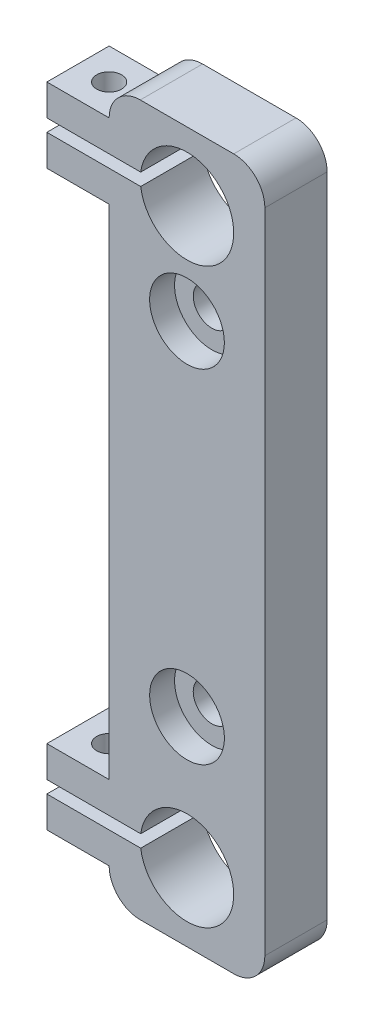
SolidWorks part; units mm, degrees
material "1.0035 (S185)"
ref_plane "前视基准面" through (0, 0, 0) normal (0, 0, 1) x (1, 0, 0)
ref_plane "上视基准面" through (0, 0, 0) normal (0, 1, 0) x (1, 0, 0)
ref_plane "右视基准面" through (0, 0, 0) normal (1, 0, 0) x (0, 0, -1)
sketch "草图1" plane through (0, 0, 0) normal (0, 0, 1) x (1, 0, 0)
  line L1 (-7.5, -57) -> (7.5, -57)
  line L2 (-12.5, -52) -> (-12.5, 52)
  line L3 (-7.5, 57) -> (7.5, 57)
  line L4 (12.5, -52) -> (12.5, 52)
  line L5 (-12.5, -57) -> (12.5, 57) construction
  line L6 (-12.5, 57) -> (12.5, -57) construction
  arc A0 (-7.5, -57) -> (-12.5, -52) centre (-7.5, -52) cw
  arc A1 (7.5, -57) -> (12.5, -52) centre (7.5, -52) ccw
  arc A2 (7.5, 57) -> (12.5, 52) centre (7.5, 52) cw
  arc A3 (-12.5, 52) -> (-7.5, 57) centre (-7.5, 52) cw
  point P0 (0, 0)
  dimension "D3" = 5
  dimension "D1" = 25
  dimension "D2" = 114
extrude "凸台-拉伸1" add sketch "草图1" along normal blind 10
sketch "草图2" plane through (0, 0, 10) normal (0, 0, 1) x (1, 0, 0)
  line L1 (-12.5, 0) -> (12.5, 0) construction
  line L2 (-12.5, 52) -> (-12.5, -52) construction
  line L3 (12.5, -52) -> (12.5, 52) construction
  circle A0 centre (0, 46) radius 7.5
  circle A1 centre (0, -46) radius 7.5
  dimension "D1" = 15
  dimension "D2" = 92
sketch "草图4" plane through (0, 0, 10) normal (0, 0, 1) x (1, 0, 0)
  line L0 (12.5, 0) -> (-12.5, 0) construction
  line L1 (12.5, -52) -> (12.5, 52) construction
  line L2 (-12.5, 52) -> (-12.5, -52) construction
  line L3 (-7.5, -57) -> (7.5, -57) construction
  circle A0 centre (0, 30) radius 3
  circle A4 centre (0, -25) radius 3
  dimension "D1" = 6
  dimension "D2" = 30
  dimension "D3" = 32
extrude "切除-拉伸1" cut sketch "草图4" against normal through all
extrude "切除-拉伸3" cut sketch "草图2" against normal through all
sketch "草图6" plane through (0, 0, 10) normal (0, 0, 1) x (1, 0, 0)
  line L0 (0, 21.3801) -> (0, -24.2411) construction
  line L1 (-25.5484, 0) -> (25.3307, 0) construction
  circle A0 centre (0, 30) radius 6
  circle A4 centre (0, -25) radius 6
  circle A5 centre (0, -25) radius 3 construction
  dimension "D1" = 12
extrude "切除-拉伸4" cut sketch "草图6" against normal blind 4
sketch "草图7" plane through (0, 0, 0) normal (0, 0, 1) x (1, 0, 0)
  line L0 (0, 46) -> (-27.6671, 46) construction
  line L1 (-12.5, 52) -> (-12.5, -52) construction
  line L2 (-12.5, 47) -> (-22.5, 47)
  line L3 (-12.5, 47) -> (-12.5, 52)
  line L4 (-12.5, 52) -> (-22.5, 52)
  line L5 (-22.5, 47) -> (-22.5, 52)
  line L6 (-22.5, 45) -> (-22.5, 40)
  line L7 (-12.5, 40) -> (-22.5, 40)
  line L8 (-12.5, 45) -> (-12.5, 40)
  line L9 (-12.5, 45) -> (-22.5, 45)
  line L10 (0, 0) -> (-29.1276, 0) construction
  line L11 (0, -46) -> (-27.6671, -46) construction
  line L12 (-12.5, -45) -> (-22.5, -45)
  line L13 (-12.5, -45) -> (-12.5, -40)
  line L14 (-12.5, -40) -> (-22.5, -40)
  line L15 (-22.5, -45) -> (-22.5, -40)
  line L16 (-22.5, -47) -> (-22.5, -52)
  line L17 (-12.5, -52) -> (-22.5, -52)
  line L18 (-12.5, -47) -> (-12.5, -52)
  line L19 (-12.5, -47) -> (-22.5, -47)
  dimension "D1" = 5
  dimension "D2" = 10
  dimension "D3" = 2
extrude "凸台-拉伸2" add sketch "草图7" along normal up to surface (10 mm away) up to face at (6, 30, 10)
sketch "草图8" plane through (0, 0, 0) normal (0, 0, 1) x (1, 0, 0)
  line L0 (-12.5, 47) -> (-22.5, 47) construction
  line L1 (-22.5, 45) -> (-2.5, 45)
  line L2 (-22.5, 45) -> (-22.5, 47)
  line L3 (-22.5, 47) -> (-2.5, 47)
  line L4 (-2.5, 45) -> (-2.5, 47)
  line L5 (0, 0) -> (-42.9645, 0) construction
  line L6 (-2.5, -45) -> (-2.5, -47)
  line L7 (-22.5, -47) -> (-2.5, -47)
  line L8 (-22.5, -45) -> (-22.5, -47)
  line L9 (-22.5, -45) -> (-2.5, -45)
  dimension "D1" = 20
extrude "切除-拉伸6" cut sketch "草图8" along normal through all
sketch "草图10" plane through (0, 0, 0) normal (0, 1, 0) x (1, 0, 0)
  line L0 (-12.5, 0) -> (-22.5, 0) construction
  line L1 (-22.5, -10) -> (-22.5, 0) construction
  circle A0 centre (-17.5, -5) radius 2
  dimension "D1" = 4
  dimension "D2" = 5
  dimension "D3" = 5
extrude "切除-拉伸7" cut sketch "草图10" against normal through all both and the other way through all
